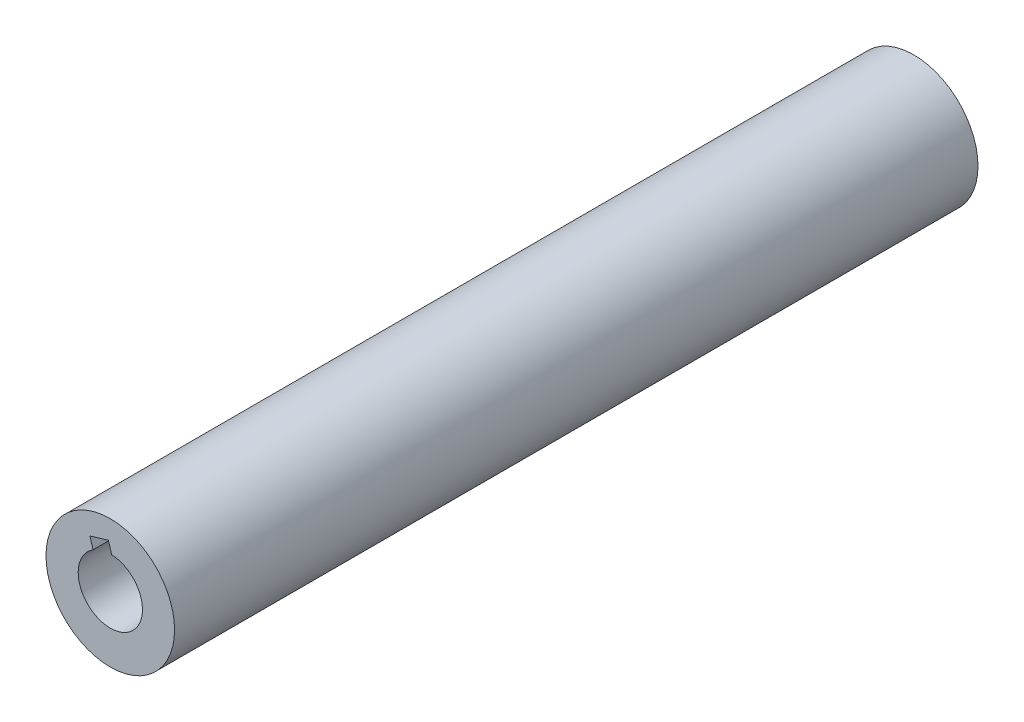
SolidWorks part; units mm, degrees
ref_plane "前基準面" through (0, 0, 0) normal (0, 0, 1) x (1, 0, 0)
ref_plane "上基準面" through (0, 0, 0) normal (0, 1, 0) x (1, 0, 0)
ref_plane "右基準面" through (0, 0, 0) normal (1, 0, 0) x (0, 0, -1)
sketch "草圖1" plane through (0, 0, 0) normal (0, 0, 1) x (1, 0, 0)
  circle A0 centre (0, 0) radius 10
  circle A1 centre (-0.0157, -0.4998) radius 20
extrude "填料-伸長1" add sketch "草圖1" along normal up to surface (250 mm away) from surface
ref_plane "平面1" through (-2.8939, 9.5721, 0) normal (0.2894, -0.9572, 0) x (0, 0, 1)
sketch "草圖2" plane through (-2.8939, 9.5721, 0) normal (0.2894, -0.9572, 0) x (0, 0, 1)
  line L0 (-150, 20.1597) -> (-150, 21.505) construction
  line L1 (-275, 2.7033) -> (-25, 2.7033)
  line L2 (-275, 2.7033) -> (-275, -3.2967)
  line L3 (-275, -3.2967) -> (-25, -3.2967)
  line L4 (-25, 2.7033) -> (-25, -3.2967)
  line L5 (-25, 20.1597) -> (-275, 20.1597) construction
  line L6 (-150, 2.7033) -> (-150, 8.2789) construction
  dimension "D1" = 6
  dimension "D2" = 250
extrude "除料-伸長1" cut sketch "草圖2" along normal up to next from offset 3
